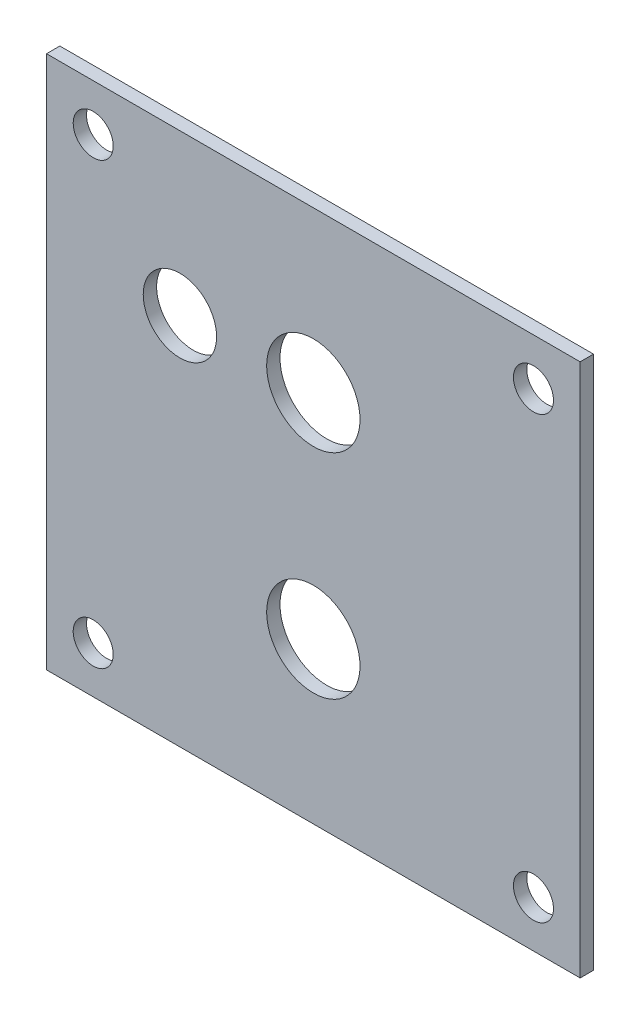
SolidWorks part; units mm, degrees
ref_plane "Front Plane" through (0, 0, 0) normal (0, 0, 1) x (1, 0, 0)
ref_plane "Top Plane" through (0, 0, 0) normal (0, 1, 0) x (1, 0, 0)
ref_plane "Right Plane" through (0, 0, 0) normal (1, 0, 0) x (0, 0, -1)
sketch "Sketch1" plane through (0, 0, 0) normal (0, 0, 1) x (1, 0, 0)
  line L1 (-63.5, 63.5) -> (63.5, 63.5)
  line L2 (-63.5, 63.5) -> (-63.5, -63.5)
  line L3 (-63.5, -63.5) -> (63.5, -63.5)
  line L4 (63.5, 63.5) -> (63.5, -63.5)
  line L5 (-63.5, 63.5) -> (63.5, -63.5) construction
  line L6 (-63.5, -63.5) -> (63.5, 63.5) construction
  point P0 (0, 0)
  dimension "D1" = 127
  dimension "D2" = 127
extrude "Boss-Extrude1" add sketch "Sketch1" along normal blind 3.175
sketch "Sketch2" plane through (0, 0, 0) normal (0, 0, -1) x (-1, 0, 0)
  line L4 (-63.5, 63.5) -> (63.5, 63.5) construction
  line L5 (63.5, -63.5) -> (-63.5, -63.5) construction
  line L6 (-63.5, -63.5) -> (-63.5, 63.5) construction
  line L7 (63.5, 63.5) -> (63.5, -63.5) construction
  circle A0 centre (0, 25.4) radius 11.1125
  circle A1 centre (31.75, 25.4) radius 8.7312
  circle A2 centre (0, -25.4) radius 11.1125
  dimension "D1" = 22.225
  dimension "D2" = 38.1
  dimension "D4" = 17.4625
  dimension "D5" = 38.1
  dimension "D6" = 63.5
  dimension "D7" = 22.225
  dimension "D8" = 63.5
  dimension "D9" = 31.75
  dimension "D3" = 38.1
extrude "Cut-Extrude1" cut sketch "Sketch2" against normal up to surface (3.175 mm away) up to face at (0, 0, 3.175)
sketch "Sketch3" plane through (0, 0, 0) normal (0, 0, -1) x (-1, 0, 0)
  line L0 (-63.5, 63.5) -> (63.5, 63.5) construction
  line L1 (63.5, 63.5) -> (63.5, -63.5) construction
  line L2 (63.5, 0) -> (-63.5, 0) construction
  line L3 (-63.5, -63.5) -> (-63.5, 63.5) construction
  line L4 (0, -63.5) -> (0, 63.5) construction
  line L5 (63.5, -63.5) -> (-63.5, -63.5) construction
  circle A0 centre (52.3875, 52.3875) radius 4.7625
  circle A1 centre (52.3875, -52.3875) radius 4.7625
  circle A2 centre (-52.3875, 52.3875) radius 4.7625
  circle A3 centre (-52.3875, -52.3875) radius 4.7625
  dimension "D1" = 9.525
  dimension "D2" = 11.1125
  dimension "D3" = 11.1125
extrude "Cut-Extrude2" cut sketch "Sketch3" against normal up to surface (3.175 mm away) up to face at (11.1125, -25.4, 3.175)
